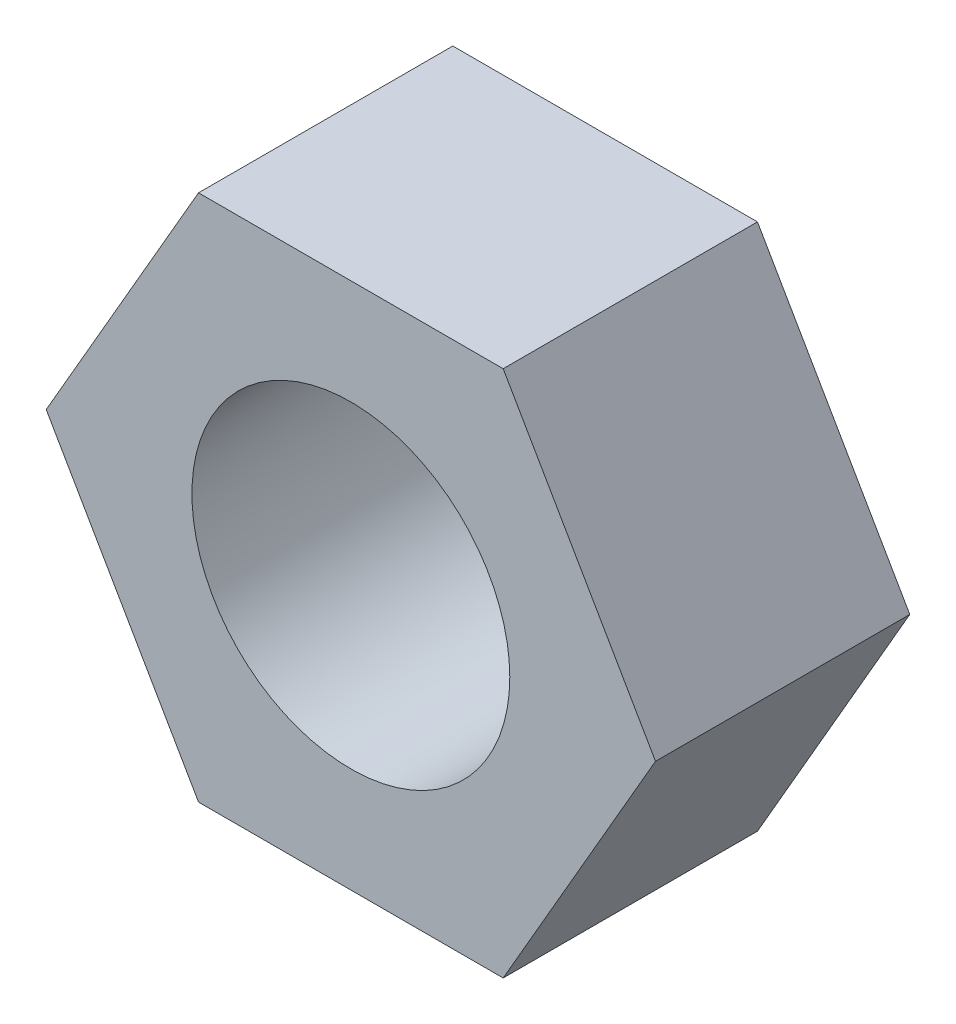
SolidWorks part; units mm, degrees
ref_plane "Спереди" through (0, 0, 0) normal (0, 0, 1) x (1, 0, 0)
ref_plane "Сверху" through (0, 0, 0) normal (0, 1, 0) x (1, 0, 0)
ref_plane "Справа" through (0, 0, 0) normal (1, 0, 0) x (0, 0, -1)
other "Configuration Table"
sketch "Шестигранник_эскиз" plane through (0, 0, 0) normal (0, 0, 1) x (1, 0, 0)
  line L0 (4.792, 0) -> (2.396, 4.15)
  line L1 (2.396, 4.15) -> (-2.396, 4.15)
  line L2 (-2.396, 4.15) -> (-4.792, 0)
  line L3 (-4.792, 0) -> (-2.396, -4.15)
  line L4 (-2.396, -4.15) -> (2.396, -4.15)
  line L5 (2.396, -4.15) -> (4.792, 0)
  circle A0 centre (0, 0) radius 4.15 construction
  dimension "D1" = 8.3
extrude "Корпус_гайки" add sketch "Шестигранник_эскиз" along normal blind 4
sketch "Отверстие_эскиз" plane through (0, 0, 0) normal (0, 0, 1) x (1, 0, 0)
  circle A0 centre (0, 0) radius 2.5
  dimension "D1" = 5
extrude "Отверстие_под_M5" cut sketch "Отверстие_эскиз" against normal through all and the other way through all
cosmetic thread "Резьба_M5x0_8_6H" parameters "D2"=5
equation "\"Гайка под ключ\"= 8"
equation "\"Гайка высота\"= 4"
equation "\"Гайка отверстие под резьбу\"=5"
equation "\"Гайка диаметр резьбы\"= 5"
equation "\"Гайка шаг резьбы\"= 0.8"
equation "\"Гайка фаска отверстия\"= 0.4"
equation "\"D1@Корпус_гайки\" = \"Гайка высота\""
equation "\"D1@Отверстие_эскиз\" = \"Гайка отверстие под резьбу\""
